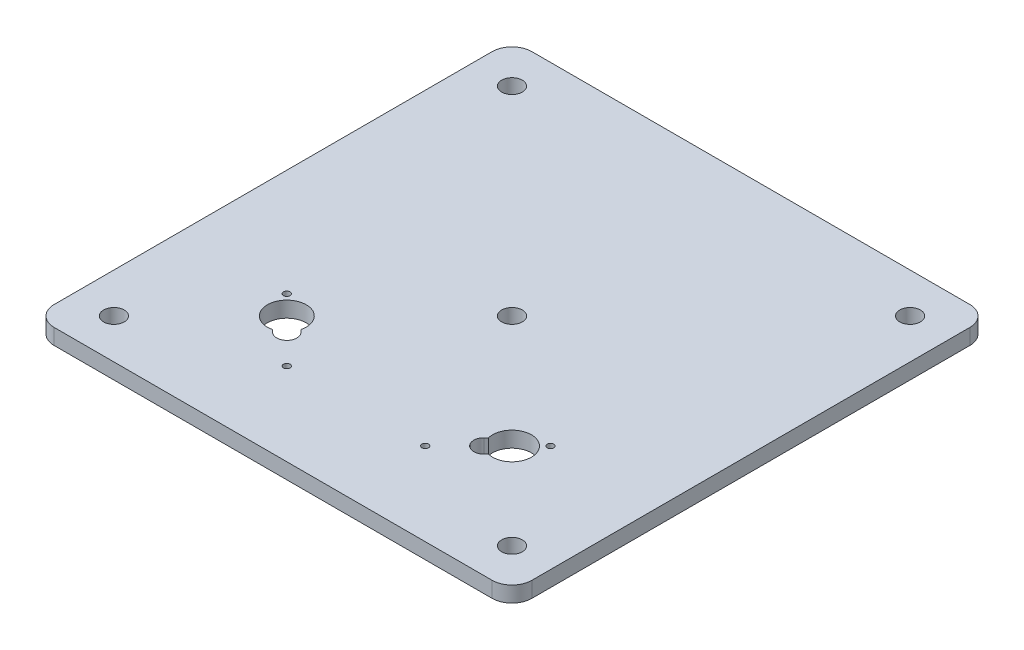
SolidWorks part; units mm, degrees
ref_plane "Front Plane" through (0, 0, 0) normal (0, 0, 1) x (1, 0, 0)
ref_plane "Top Plane" through (0, 0, 0) normal (0, 1, 0) x (1, 0, 0)
ref_plane "Right Plane" through (0, 0, 0) normal (1, 0, 0) x (0, 0, -1)
sketch "Sketch1" plane through (0, 0, 0) normal (0, 1, 0) x (1, 0, 0)
  line L0 (0, 76.2) -> (0, -76.2) construction
  line L1 (-69.85, 76.2) -> (69.85, 76.2)
  line L2 (-76.2, 69.85) -> (-76.2, -69.85)
  line L3 (-69.85, -76.2) -> (69.85, -76.2)
  line L4 (76.2, 69.85) -> (76.2, -69.85)
  line L5 (-76.2, 76.2) -> (76.2, -76.2) construction
  line L6 (-76.2, -76.2) -> (76.2, 76.2) construction
  line L7 (-76.2, 0) -> (76.2, 0) construction
  arc A0 (-76.2, -69.85) -> (-69.85, -76.2) centre (-69.85, -69.85) ccw
  arc A1 (69.85, -76.2) -> (76.2, -69.85) centre (69.85, -69.85) ccw
  arc A2 (69.85, 76.2) -> (76.2, 69.85) centre (69.85, 69.85) cw
  arc A3 (-69.85, 76.2) -> (-76.2, 69.85) centre (-69.85, 69.85) ccw
  circle A5 centre (63.5, 63.5) radius 3.302
  circle A6 centre (63.5, -63.5) radius 3.302
  circle A7 centre (-63.5, -63.5) radius 3.302
  circle A8 centre (-63.5, 63.5) radius 3.302
  circle A9 centre (0, 0) radius 3.302
  circle A10 centre (0, 0) radius 38.1 construction
  circle A11 centre (-35.921, -35.921) radius 12.7 construction
  circle A12 centre (35.921, -35.921) radius 12.7 construction
  point P0 (0, 0)
  dimension "D3" = 6.35
  dimension "D4" = 12.7
  dimension "D5" = 6.604
  dimension "D7" = 6.604
  dimension "D8" = 76.2
  dimension "D9" = 25.4
  dimension "D1" = 152.4
  dimension "D2" = 152.4
  dimension "D6" = 12.7
sketch "Sketch2" plane through (0, 0, 0) normal (0, 1, 0) x (1, 0, 0)
  line L0 (-29.5217, -38.502) -> (-30.4622, -37.5615) construction
  line L1 (-33.3401, -42.3203) -> (-34.2806, -41.3799) construction
  line L2 (-39.9515, -31.8905) -> (-29.5217, -42.3203) construction
  line L3 (-76.2, -76.2) -> (76.2, 76.2) construction
  line L4 (0, -76.2) -> (0, 76.2) construction
  line L5 (39.9515, -31.8905) -> (29.5217, -42.3203) construction
  line L6 (33.3401, -42.3203) -> (34.2806, -41.3799) construction
  line L7 (29.5217, -38.502) -> (30.4622, -37.5615) construction
  line L8 (-39.9162, -31.9259) -> (35315.4229, -35387.2649) construction
  line L9 (-33.6936, -42.6739) -> (-34.4288, -41.9388)
  line L10 (-29.1682, -38.1484) -> (-29.9033, -37.4133)
  line L11 (33.6936, -42.6739) -> (34.4288, -41.9388)
  line L12 (29.1682, -38.1484) -> (29.9033, -37.4133)
  arc A0 (33.3401, -42.3203) -> (29.5217, -38.502) centre (31.4309, -40.4112) cw construction
  arc A2 (-30.4622, -37.5615) -> (-34.2806, -41.3799) centre (-35.921, -35.921) ccw construction
  arc A3 (-33.3401, -42.3203) -> (-29.5217, -38.502) centre (-31.4309, -40.4112) ccw construction
  arc A4 (30.4622, -37.5615) -> (34.2806, -41.3799) centre (35.921, -35.921) cw construction
  circle A5 centre (-42.0552, -29.7869) radius 1.05
  circle A6 centre (-22.0794, -49.7626) radius 1.05
  circle A7 centre (22.0794, -49.7626) radius 1.05
  circle A8 centre (42.0552, -29.7869) radius 1.05
  arc A9 (-29.9033, -37.4133) -> (-34.4288, -41.9388) centre (-35.921, -35.921) ccw
  arc A10 (-33.6936, -42.6739) -> (-29.1682, -38.1484) centre (-31.4309, -40.4112) ccw
  arc A11 (33.6936, -42.6739) -> (29.1682, -38.1484) centre (31.4309, -40.4112) cw
  arc A12 (29.9033, -37.4133) -> (34.4288, -41.9388) centre (35.921, -35.921) cw
  point P8 (-29.5217, -42.3203)
  point P10 (-39.9515, -31.8905)
  point P31 (-47.3132, -24.5288)
  point P33 (-22.9483, -48.8938)
  dimension "D1" = 90
  dimension "D2" = 11.4
  dimension "D4" = 2.7
  dimension "D8" = 2.1
  dimension "D9" = 28.25
  dimension "D3" = 14.75
  dimension "D5" = 2.7
  dimension "D6" = 2.7
  dimension "D7" = 8.675
  dimension "D10" = 0.5
extrude "Boss-Extrude1" add sketch "Sketch1" along normal blind 5
extrude "Cut-Extrude2" cut sketch "Sketch2" along normal through all
